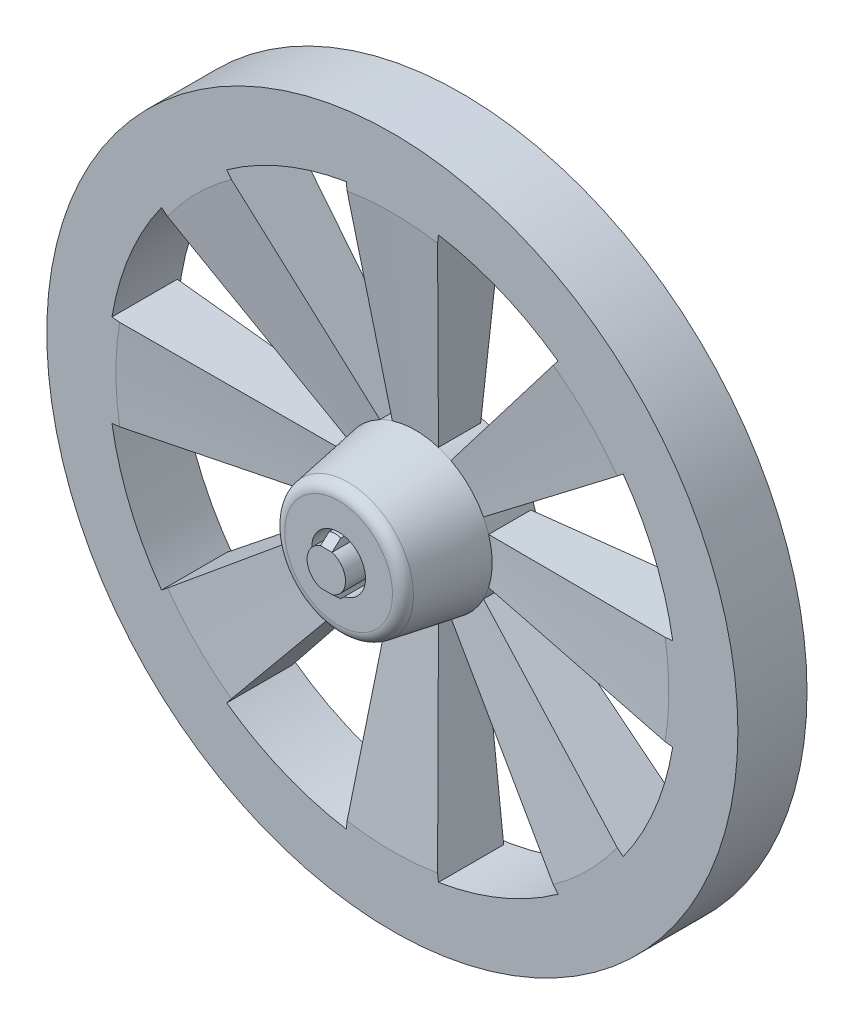
SolidWorks part; units mm, degrees
ref_plane "Front Plane" through (0, 0, 0) normal (0, 0, 1) x (1, 0, 0)
ref_plane "Top Plane" through (0, 0, 0) normal (0, 1, 0) x (1, 0, 0)
ref_plane "Right Plane" through (0, 0, 0) normal (1, 0, 0) x (0, 0, -1)
sketch "Sketch1" plane through (0, 0, 0) normal (0, 0, 1) x (1, 0, 0)
  circle A0 centre (0, 0) radius 571.5
  circle A1 centre (0, 0) radius 469.9
  dimension "D1" = 101.6
  dimension "D2" = 1143
extrude "Boss-Extrude1" add sketch "Sketch1" along normal blind 114.3
sketch "Sketch2" plane through (0, 0, 114.3) normal (0, 0, 1) x (1, 0, 0)
  line L0 (-76.2, 463.6805) -> (-38.1, 121.1503)
  line L1 (76.2, 463.6805) -> (38.1, 121.1503)
  circle A0 centre (0, 0) radius 469.9 construction
  circle A1 centre (0, 0) radius 127
  circle M2 centre (0, 0) radius 469.9
  dimension "D1" = 152.4
  dimension "D3" = 254
  dimension "D2" = 76.2
extrude "Boss-Extrude2" add sketch "Sketch2" against normal blind 107.95 contours A1 L1 L0 M2
pattern_circular "CirPattern2" count 8 over 360 about axis through (0, 0, 0) along (0, 0, 1) of "Boss-Extrude2"
ref_plane "Plane4" through (0, 0, 76.2) normal (0, 0, 1) x (1, 0, 0)
sketch "Sketch17" plane through (0, 0, 76.2) normal (0, 0, 1) x (1, 0, 0)
  circle A0 centre (0, 0) radius 127
sketch "Sketch18" plane through (0, 0, 114.3) normal (0, 0, 1) x (1, 0, 0)
  line L0 (-463.6805, 76.2) -> (-121.1503, 38.1) construction
  circle A0 centre (0, 0) radius 457.2177
  point P3 (-451.0583, 74.796)
  dimension "D1" = 12.7
loft "Cut-Loft1" cut profiles "Sketch18", "Sketch17"
sketch "Sketch9" plane through (0, 0, 0) normal (0, 0, 1) x (1, 0, 0)
  circle A0 centre (0, 0) radius 127
  arc A2 (38.1, 121.1503) -> (-38.1, 121.1503) centre (0, 0) ccw construction
  point P4 (0, 127)
  dimension "D1" = 254
extrude "Boss-Extrude4" add sketch "Sketch9" along normal up to vertex (76.2 mm away)
sketch "Sketch10" plane through (0, 0, 76.2) normal (0, 0, 1) x (1, 0, 0)
  circle A0 centre (0, 0) radius 127
ref_plane "Plane3" through (0, 0, 203.2) normal (0, 0, 1) x (1, 0, 0)
sketch "Sketch11" plane through (0, 0, 203.2) normal (0, 0, 1) x (1, 0, 0)
  circle A2 centre (0, 0) radius 88.9
  circle A3 centre (0, 0) radius 88.9
  dimension "D1" = 38.1
sketch "Sketch12" plane through (0, 0, 0) normal (0, 1, 0) x (1, 0, 0)
  line L0 (-95.25, -76.2) -> (-76.2, -187.1423)
  line L1 (-127, -76.2) -> (127, -76.2) construction
  line L2 (-88.9, -203.2) -> (88.9, -203.2) construction
  arc A0 (-57.15, -203.2) -> (-76.2, -187.1423) centre (-57.15, -183.8712) cw
  point P4 (-57.15, -203.2)
  dimension "D3" = 19.05
  dimension "D1" = 95.25
  dimension "D2" = 57.15
extrude "Boss-Extrude6" add sketch "Sketch10" along normal blind 127 draft 9.74
fillet "Fillet1" radius 19.05 1 edges at (105.2002, 0, 203.2)
sketch "Sketch13" plane through (0, 0, 203.2) normal (0, 0, 1) x (1, 0, 0)
  circle A0 centre (0, 0) radius 44.45
extrude "Cut-Extrude2" cut sketch "Sketch13" against normal blind 50.8
sketch "Sketch15" plane through (0, 0, 152.4) normal (0, 0, 1) x (1, 0, 0)
  line L0 (-9.525, 43.4175) -> (-9.525, 30.2876)
  line L1 (9.525, 43.4175) -> (9.525, 30.2876)
  line L2 (-44.45, 0) -> (-31.75, 0) construction
  line L3 (9.525, -43.4175) -> (9.525, -30.2876)
  line L4 (-9.525, -43.4175) -> (-9.525, -30.2876)
  line L5 (31.75, 0) -> (44.45, 0) construction
  arc A0 (9.525, -30.2876) -> (9.525, 30.2876) centre (0, 0) ccw
  circle A1 centre (0, 0) radius 44.45 construction
  circle A2 centre (0, 0) radius 44.45 construction
  arc A3 (9.525, 43.4175) -> (-9.525, 43.4175) centre (0, 0) ccw
  arc A4 (9.525, -43.4175) -> (-9.525, -43.4175) centre (0, 0) cw
  arc A5 (-9.525, 30.2876) -> (-9.525, -30.2876) centre (0, 0) ccw
  dimension "D1" = 63.5
  dimension "D2" = 19.05
extrude "Boss-Extrude9" add sketch "Sketch15" along normal blind 71.12
sketch "Sketch16" plane through (0, 0, 0) normal (1, 0, 0) x (0, 0, -1)
  line L0 (-223.52, 30.2876) -> (-208.28, 44.45)
  line L1 (-203.2, 44.45) -> (-223.52, 44.45) construction
  line L2 (-208.28, 44.45) -> (-223.52, 44.45)
  line L3 (-223.52, 44.45) -> (-223.52, 43.4175) construction
  line L4 (-223.52, 44.45) -> (-223.52, 30.2876)
  line L5 (-223.52, 0) -> (-135.7445, 0) construction
  line L6 (-223.52, 30.2876) -> (-223.52, -30.2876) construction
  line L7 (-223.52, -44.45) -> (-223.52, -30.2876)
  line L8 (-208.28, -44.45) -> (-223.52, -44.45)
  line L9 (-223.52, -30.2876) -> (-208.28, -44.45)
  dimension "D1" = 15.24
extrude "Cut-Extrude3" cut sketch "Sketch16" against normal blind 71.12 and the other way blind 71.12
sketch "Sketch19" plane through (0, 0, 0) normal (0, 0, -1) x (-1, 0, 0)
  circle A0 centre (0, 0) radius 63.5
extrude "Cut-Extrude4" cut sketch "Sketch19" against normal blind 25.4
